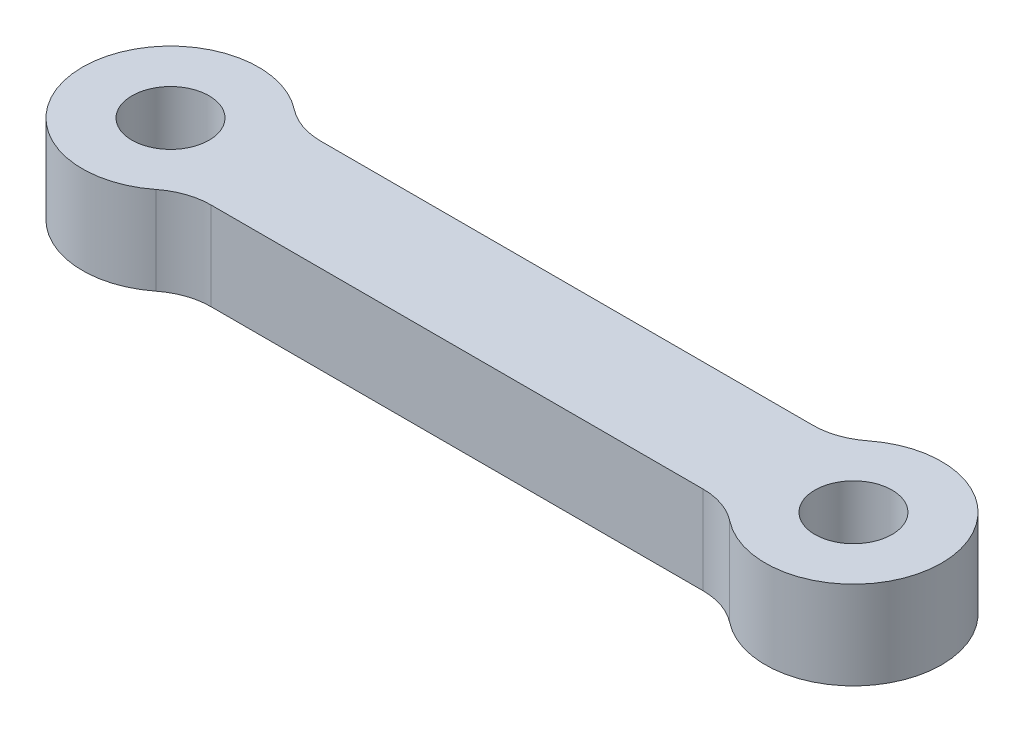
SolidWorks part; units mm, degrees
ref_plane "Front Plane" through (0, 0, 0) normal (0, 0, 1) x (1, 0, 0)
ref_plane "Top Plane" through (0, 0, 0) normal (0, 1, 0) x (1, 0, 0)
ref_plane "Right Plane" through (0, 0, 0) normal (1, 0, 0) x (0, 0, -1)
sketch "Sketch1" plane through (0, 0, 0) normal (0, 1, 0) x (1, 0, 0)
  line L0 (-998.25, 0) -> (1.75, 0) construction
  line L2 (27.8775, 2.5) -> (3.1225, 2.5)
  line L3 (27.8775, -2.5) -> (3.1225, -2.5)
  line L4 (29.25, 0) -> (50001.75, 0) construction
  arc A0 (3.1225, 2.5) -> (3.1225, -2.5) centre (0, 0) ccw
  circle A1 centre (0, 0) radius 1.75
  arc A2 (27.8775, -2.5) -> (27.8775, 2.5) centre (31, 0) ccw
  circle A3 centre (31, 0) radius 1.75
  dimension "D1" = 8
  dimension "D2" = 3.5
  dimension "D3" = 8
  dimension "D4" = 3.5
  dimension "D5" = 31
  dimension "D6" = 2.5
extrude "Boss-Extrude1" add sketch "Sketch1" along normal blind 4
fillet "Fillet1" radius 3 4 edges at (27.8775, 2, -2.5) (3.1225, 2, -2.5) (27.8775, 2, 2.5) (3.1225, 2, 2.5)
